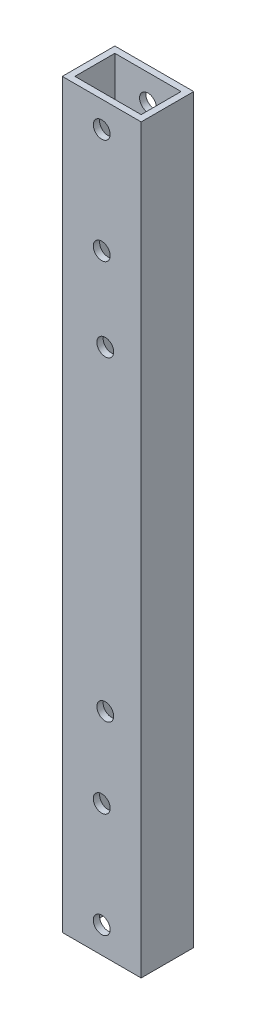
SolidWorks part; units mm, degrees
ref_plane "正面" through (0, 0, 0) normal (0, 0, 1) x (1, 0, 0)
ref_plane "平面" through (0, 0, 0) normal (0, 1, 0) x (1, 0, 0)
ref_plane "右側面" through (0, 0, 0) normal (1, 0, 0) x (0, 0, -1)
sketch "ｽｹｯﾁ1" plane through (0, 0, 0) normal (0, 1, 0) x (1, 0, 0)
  line L0 (-6.3, 3.8) -> (6.3, 3.8)
  line L1 (-7.5, 5) -> (7.5, 5)
  line L2 (-7.5, 5) -> (-7.5, -5)
  line L3 (-7.5, -5) -> (7.5, -5)
  line L4 (7.5, 5) -> (7.5, -5)
  line L5 (-7.5, 5) -> (7.5, -5) construction
  line L6 (-7.5, -5) -> (7.5, 5) construction
  line L7 (6.3, 3.8) -> (6.3, -3.8)
  line L8 (-6.3, -3.8) -> (6.3, -3.8)
  line L9 (-6.3, 3.8) -> (-6.3, -3.8)
  point P0 (0, 0)
  dimension "D1" = 15
  dimension "D2" = 10
  dimension "D3" = 1.2
extrude "ﾎﾞｽ - 押し出し1" add sketch "ｽｹｯﾁ1" along normal mid plane 141
sketch "ｽｹｯﾁ2" plane through (0, 0, -5) normal (0, 0, -1) x (-1, 0, 0)
  line L0 (0, 0) -> (-7.5, 0) construction
  line L1 (-7.5, 70.5) -> (-7.5, -70.5) construction
  line L2 (0, 0) -> (0, -70.5) construction
  line L3 (-7.5, -70.5) -> (7.5, -70.5) construction
  circle A0 centre (0, -65.5) radius 1.6
  circle A1 centre (0, -45.5) radius 1.6
  circle A2 centre (0, 45.5) radius 1.6
  circle A3 centre (0, 65.5) radius 1.6
  dimension "D1" = 3.2
  dimension "D2" = 3.2
  dimension "D3" = 5
  dimension "D4" = 20
extrude "ｶｯﾄ - 押し出し1" cut sketch "ｽｹｯﾁ2" against normal blind 100
sketch "ｽｹｯﾁ3" plane through (0, 0, -5) normal (0, 0, -1) x (-1, 0, 0)
  circle A0 centre (-0.6765, -30) radius 1.6 construction
  circle A1 centre (-0.6765, 30) radius 1.6 construction
  circle A2 centre (-0.6765, -30) radius 1.6
  circle A3 centre (-0.6765, 30) radius 1.6
extrude "ｶｯﾄ - 押し出し2" cut sketch "ｽｹｯﾁ3" against normal blind 10
